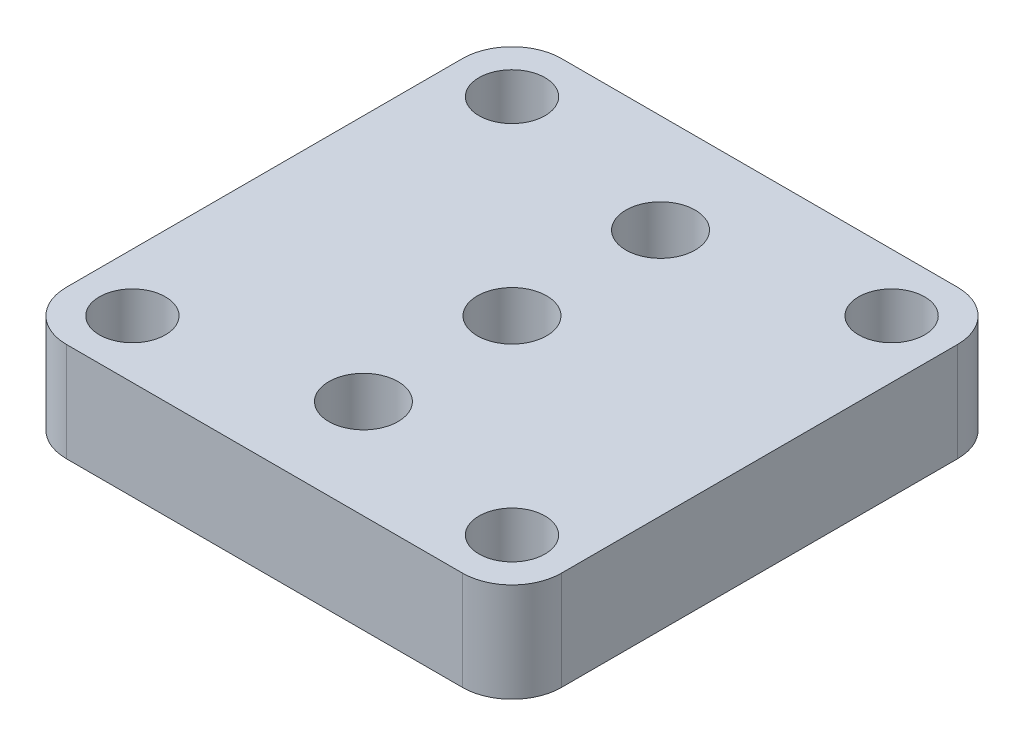
SolidWorks part; units mm, degrees
ref_plane "Front Plane" through (0, 0, 0) normal (0, 0, 1) x (1, 0, 0)
ref_plane "Top Plane" through (0, 0, 0) normal (0, 1, 0) x (1, 0, 0)
ref_plane "Right Plane" through (0, 0, 0) normal (1, 0, 0) x (0, 0, -1)
sketch "Sketch2" plane through (0, 0, 0) normal (0, 1, 0) x (1, 0, 0)
  line L1 (-12, -15) -> (12, -15)
  line L2 (-15, -12) -> (-15, 12)
  line L3 (-12, 15) -> (12, 15)
  line L4 (15, -12) -> (15, 12)
  line L5 (-15, -15) -> (15, 15) construction
  line L6 (-15, 15) -> (15, -15) construction
  arc A0 (15, 12) -> (12, 15) centre (12, 12) ccw
  arc A1 (12, -15) -> (15, -12) centre (12, -12) ccw
  arc A2 (-12, -15) -> (-15, -12) centre (-12, -12) cw
  arc A3 (-15, 12) -> (-12, 15) centre (-12, 12) cw
  point P0 (0, 0)
  point P18 (-11.5, 11.5)
  point P22 (11.5, 11.5)
  point P23 (11.5, -11.5)
  point P24 (-11.5, -11.5)
  point P25 (0, 0)
  dimension "D3" = 3
  dimension "D1" = 30
  dimension "D2" = 30
  dimension "D4" = 3.5
  dimension "D5" = 3.5
  dimension "D6" = 4
extrude "Boss-Extrude1" add sketch "Sketch2" against normal blind 6
hole_wizard "M5x0.8 Tapped Hole1" positions "Sketch6" profile "Sketch5" tap size "M5x0.8" standard "ANSI Metric" end condition through all
sketch "Sketch6" plane through (0, 0, 0) normal (0, 1, 0) x (1, 0, 0)
  point P0 (0, 0)
  point P8 (0, 9)
  point P10 (0, -9)
  dimension "D1" = 9
  dimension "D2" = 9
cosmetic thread "Hole Thread1" parameters "D2"=5
sketch "Sketch5" plane through (0, 0, 0) normal (1, 0, 0) x (0, 0, 1)
  line L0 (0, 0) -> (0, 6)
  line L1 (0, 6) -> (2.1, 6)
  line L2 (2.1, 6) -> (2.1, 0)
  line L5 (2.1, 0) -> (0, 0)
  line L11 (0, -6.35) -> (0, 107.95) construction
  dimension "Thru Tap Drill Dia." = 4.2
  dimension "Thru Tap Drill Depth" = 6
cosmetic thread "Hole Thread2" parameters "D2"=5
cosmetic thread "Hole Thread3" parameters "D2"=5
hole_wizard "Ø4.0 (4) Diameter Hole1" positions "Sketch8" profile "Sketch7" hole size "Ø4.0" standard "ANSI Metric"
sketch "Sketch8" plane through (0, 0, 0) normal (0, 1, 0) x (1, 0, 0)
  point P0 (-11.5, -11.5)
  point P3 (-11.5, 11.5)
  point P6 (11.5, 11.5)
  point P9 (11.5, -11.5)
sketch "Sketch7" plane through (-11.5, 0, 11.5) normal (1, 0, 0) x (0, 0, 1)
  line L0 (0, 0) -> (0, 11.2017)
  line L1 (0, 11.2017) -> (2, 10)
  line L2 (2, 10) -> (2, 0)
  line L5 (2, 0) -> (0, 0)
  line L10 (0, 11.2017) -> (-2, 10) construction
  line L11 (0, -6.35) -> (0, 107.95) construction
  dimension "Hole Dia." = 4
  dimension "Hole Depth" = 10
  dimension "Drill Angle" = 118
